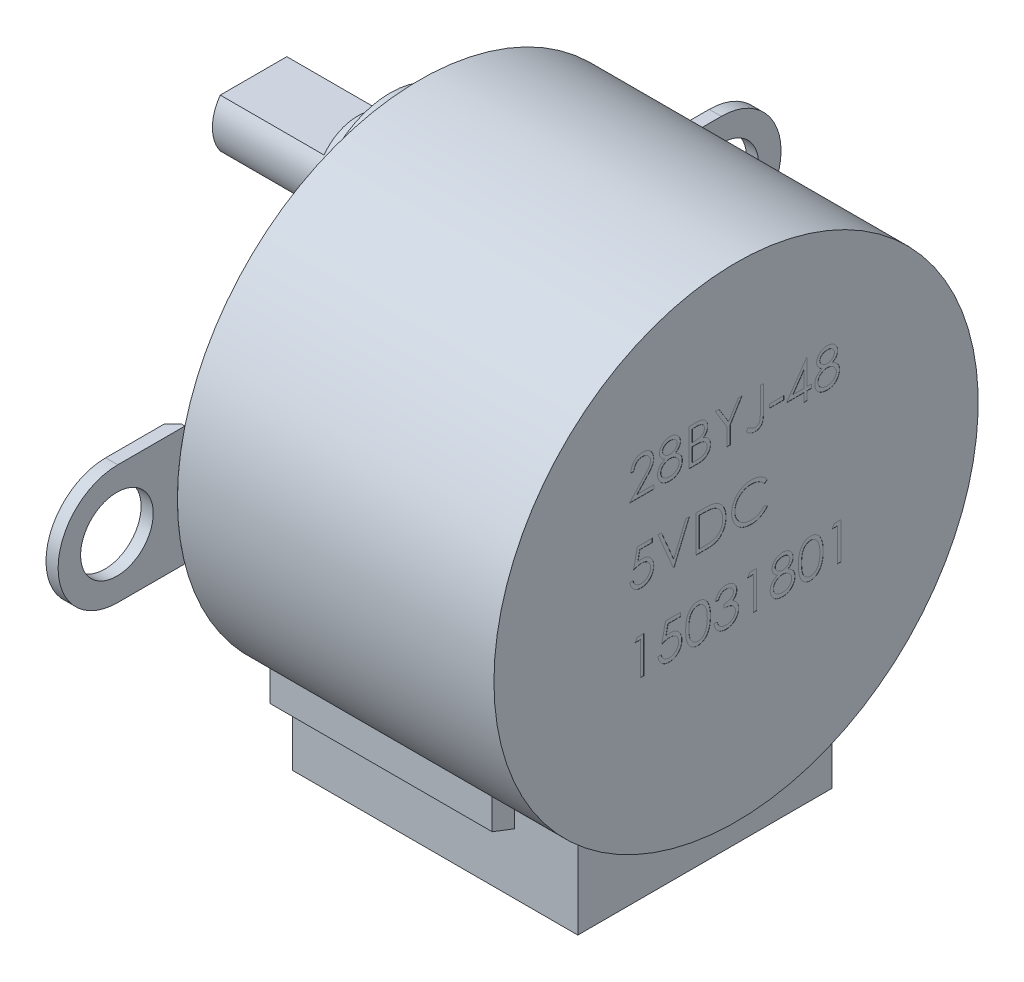
SolidWorks part; units mm, degrees
ref_plane "Front Plane" through (0, 0, 0) normal (0, 0, 1) x (1, 0, 0)
ref_plane "Top Plane" through (0, 0, 0) normal (0, 1, 0) x (1, 0, 0)
ref_plane "Right Plane" through (0, 0, 0) normal (1, 0, 0) x (0, 0, -1)
sketch "Sketch1" plane through (0, 0, 0) normal (0, 1, 0) x (1, 0, 0)
  line L0 (0, 0) -> (0, 14)
  line L1 (0, 14) -> (18.3, 14)
  line L2 (18.3, 14) -> (18.3, 0)
  line L3 (0, 0) -> (18.3, 0) construction
  line L4 (0, 0) -> (18.3, 0)
  dimension "D1" = 18.3
  dimension "D2" = 14
revolve "Revolve1" add sketch "Sketch1" angle 360 about L3
sketch "Sketch2" plane through (0, 0, 0) normal (1, 0, 0) x (0, 0, -1)
  line L0 (0, 0) -> (0, -19.0742) construction
  line L2 (7.35, -11.9154) -> (-7.35, -11.9154)
  line L3 (7.35, -11.9154) -> (7.35, -16.9)
  line L4 (7.35, -16.9) -> (-7.35, -16.9)
  line L5 (-7.35, -11.9154) -> (-7.35, -16.9)
  circle A0 centre (0, 0) radius 14 construction
  dimension "D1" = 14.7
  dimension "D2" = 30.9
extrude "Boss-Extrude1" add sketch "Sketch2" along normal blind 16.5
ref_plane "Plane1" through (9.15, 0, 0) normal (1, 0, 0) x (0, 0, -1)
sketch "Sketch3" plane through (9.15, 0, 0) normal (1, 0, 0) x (0, 0, -1)
  line L0 (0, 0) -> (0, -15.4355) construction
  line L2 (-8.65, -12.9) -> (-8.65, -9.4419)
  line L3 (-8.65, -9.4419) -> (8.65, -9.4419)
  line L4 (8.65, -12.9) -> (8.65, -9.4419)
  line L5 (-7.35, -16.9) -> (7.35, -16.9) construction
  line L6 (-8.65, -12.9) -> (-7.35, -13.4)
  line L7 (-7.35, -11.9154) -> (-7.35, -16.9) construction
  line L8 (8.65, -12.9) -> (7.35, -13.4)
  line L9 (7.35, -16.9) -> (7.35, -11.9154) construction
  line L10 (7.35, -13.4) -> (-7.35, -13.4)
  dimension "D1" = 17.3
  dimension "D3" = 3.5
extrude "Boss-Extrude2" add sketch "Sketch3" against normal up to surface (9.15 mm away) and the other way blind 3.7 up to face at (0, -7.9289, 0)
sketch "Sketch5" plane through (0, 0, 0) normal (1, 0, 0) x (0, 0, -1)
  line L0 (20.2194, 0) -> (-25.3704, 0) construction
  line L1 (-13.5683, 3.45) -> (-17.45, 3.45)
  line L2 (-13.5683, -3.45) -> (-17.45, -3.45)
  line L3 (0, 20.4579) -> (0, -24.2674) construction
  line L4 (13.5683, 3.45) -> (17.45, 3.45)
  line L5 (13.5683, -3.45) -> (17.45, -3.45)
  arc A0 (-17.45, 3.45) -> (-17.45, -3.45) centre (-17.45, 0) ccw
  arc A1 (8.65, -11.0081) -> (-8.65, -11.0081) centre (0, 0) ccw construction
  arc A2 (-13.5683, 3.45) -> (-13.5683, -3.45) centre (0, 0) ccw
  arc A3 (17.45, 3.45) -> (17.45, -3.45) centre (17.45, 0) cw
  arc A4 (13.5683, 3.45) -> (13.5683, -3.45) centre (0, 0) cw
  dimension "D1" = 6.9
  dimension "D2" = 17.45
extrude "Boss-Extrude4" add sketch "Sketch5" against normal blind 0.7
chamfer "Chamfer1" distance 0.5 angle 45 1 edges at (-0.7, 0, 14)
chamfer "Chamfer2" distance 0.5 angle 45 1 edges at (-0.7, 0, -14)
hole_wizard "Ø4.2 (4.2) Diameter Hole2" positions "Sketch8" profile "Sketch9" hole size "Ø4.2" standard "ISO" end condition through all
sketch "Sketch8" plane through (-0.7, 0, 0) normal (-1, 0, 0) x (0, 0, 1)
  line L0 (-22.4603, 0) -> (23.4314, 0) construction
  line L2 (0, 15.2402) -> (0, -20.201) construction
  point P0 (17.5, 0)
  point P2 (-17.5, 0)
  dimension "D1" = 35
sketch "Sketch9" plane through (-0.7, 0, 17.5) normal (0, 1, 0) x (0, 0, 1)
  line L0 (0, 0) -> (0, 19)
  line L1 (0, 19) -> (2.1, 19)
  line L2 (2.1, 19) -> (2.1, 0)
  line L5 (2.1, 0) -> (0, 0)
  line L11 (0, -6.35) -> (0, 107.95) construction
  dimension "Thru Hole Dia." = 4.2
  dimension "Thru Hole Depth" = 19
sketch "Sketch10" plane through (0, 0, 0) normal (-1, 0, 0) x (0, 0, 1)
  circle A0 centre (0, 8) radius 4.5
  arc A1 (8.65, -11.0081) -> (-8.65, -11.0081) centre (0, 0) ccw construction
  dimension "D1" = 9
  dimension "D2" = 6
extrude "Boss-Extrude5" add sketch "Sketch10" along normal blind 1.7
sketch "Sketch11" plane through (-1.7, 0, 0) normal (-1, 0, 0) x (0, 0, 1)
  circle A0 centre (0, 8) radius 2.38
  dimension "D1" = 4.76
extrude "Boss-Extrude6" add sketch "Sketch11" along normal blind 7.9
sketch "Sketch12" plane through (-9.6, 0, 0) normal (-1, 0, 0) x (0, 0, 1)
  line L0 (-2.38, 8) -> (3.249, 8) construction
  line L1 (-2.705, 10.7523) -> (2.7441, 10.7523)
  line L2 (-2.705, 10.7523) -> (-2.705, 9.4)
  line L3 (-2.705, 9.4) -> (2.7441, 9.4)
  line L4 (2.7441, 10.7523) -> (2.7441, 9.4)
  line L5 (-2.705, 6.6) -> (2.7441, 6.6)
  line L6 (-2.705, 6.6) -> (-2.705, 5.4465)
  line L7 (-2.705, 5.4465) -> (2.7441, 5.4465)
  line L8 (2.7441, 6.6) -> (2.7441, 5.4465)
  circle A0 centre (0, 8) radius 2.38 construction
  circle A1 centre (0, 8) radius 2.38 construction
  dimension "D1" = 2.8
extrude "Cut-Extrude1" cut sketch "Sketch12" against normal blind 6
sketch "Sketch13" plane through (18.3, 0, 0) normal (1, 0, 0) x (0, 0, -1)
  text T0 "28BYJ-48\r\n5VDC\r\n15031801" font "Century Gothic" height in points 8
extrude "Cut-Extrude2" cut sketch "Sketch13" against normal blind 0.01
sketch "Sketch14" plane through (0, -16.9, 0) normal (0, -1, 0) x (1, 0, 0)
  line L0 (0, 0) -> (4.3575, 0) construction
  line L1 (2.1, 3) -> (3.3193, 3)
  line L2 (2.1, 3) -> (2.1, -3)
  line L3 (2.1, -3) -> (3.3193, -3)
  line L4 (3.3193, 3) -> (3.3193, -3)
  line L5 (0, 7.35) -> (0, -7.35) construction
  dimension "D1" = 6
  dimension "D2" = 1.2193
  dimension "D3" = 2.1
extrude "Cut-Extrude3" cut sketch "Sketch14" against normal blind 10.01
